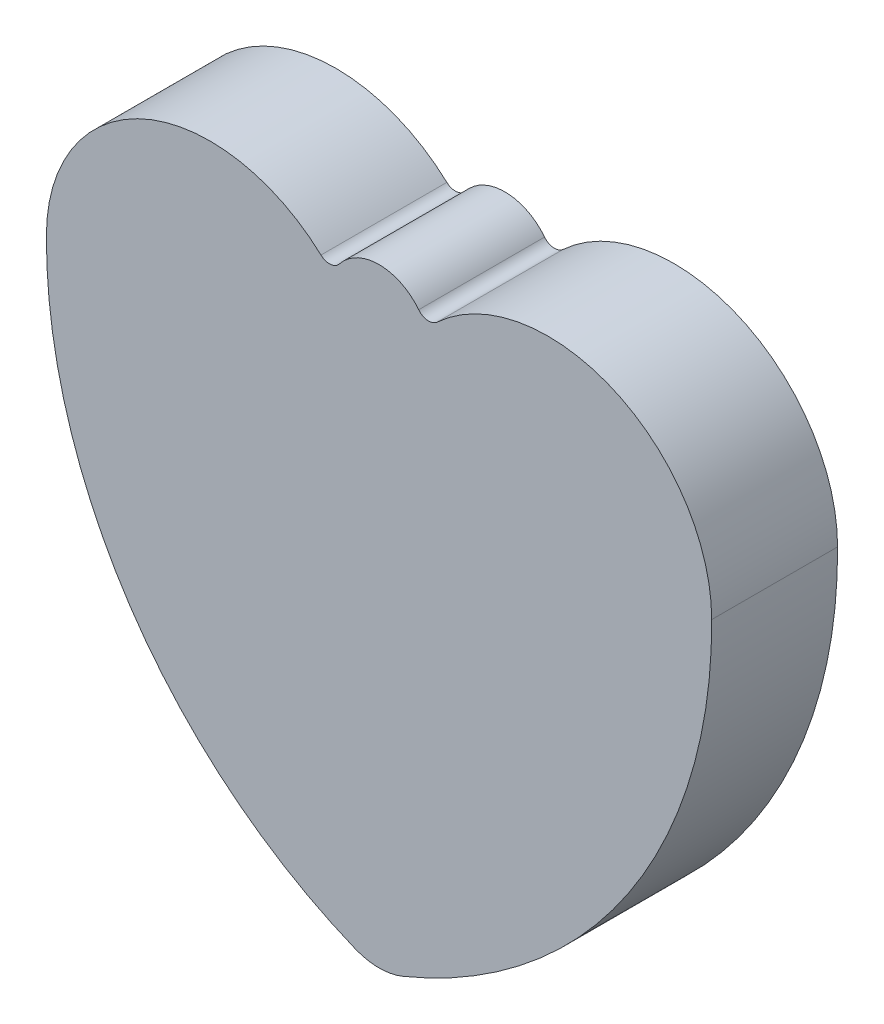
SolidWorks part; units mm, degrees
ref_plane "Płaszczyzna przednia" through (0, 0, 0) normal (0, 0, 1) x (1, 0, 0)
ref_plane "Płaszczyzna górna" through (0, 0, 0) normal (0, 1, 0) x (1, 0, 0)
ref_plane "Płaszczyzna prawa" through (0, 0, 0) normal (1, 0, 0) x (0, 0, -1)
sketch "Szkic1" plane through (0, 0, 0) normal (0, 0, 1) x (1, 0, 0)
  arc A0 (-4.6153, 22.7432) -> (-26.4259, 13.1842) centre (-13.4259, 13.1842) ccw
  arc A1 (4.6153, 22.7432) -> (26.4259, 13.1842) centre (13.4259, 13.1842) cw
  arc A2 (-1.8963, -23.6265) -> (-26.4259, 13.1842) centre (13.0914, 12.9391) cw
  arc A3 (1.8963, -23.6265) -> (26.4259, 13.1842) centre (-13.0914, 12.9391) ccw
  arc A5 (1.8963, -23.6265) -> (-1.8963, -23.6265) centre (0, -19) cw
  arc A6 (-3.1501, 22.8622) -> (3.1501, 22.8622) centre (0, 20.397) cw
  arc A7 (4.6153, 22.7432) -> (3.1501, 22.8622) centre (3.9376, 23.4785) cw
  arc A8 (-3.1501, 22.8622) -> (-4.6153, 22.7432) centre (-3.9376, 23.4785) cw
  point P0 (0, 0)
  dimension "D1" = 1
  dimension "D2" = 5
extrude "Dodanie-wyciągnięcie1" add sketch "Szkic1" along normal blind 10
scale "Skala1" scale about centroid uniform scaling yes scale factor 0.85
